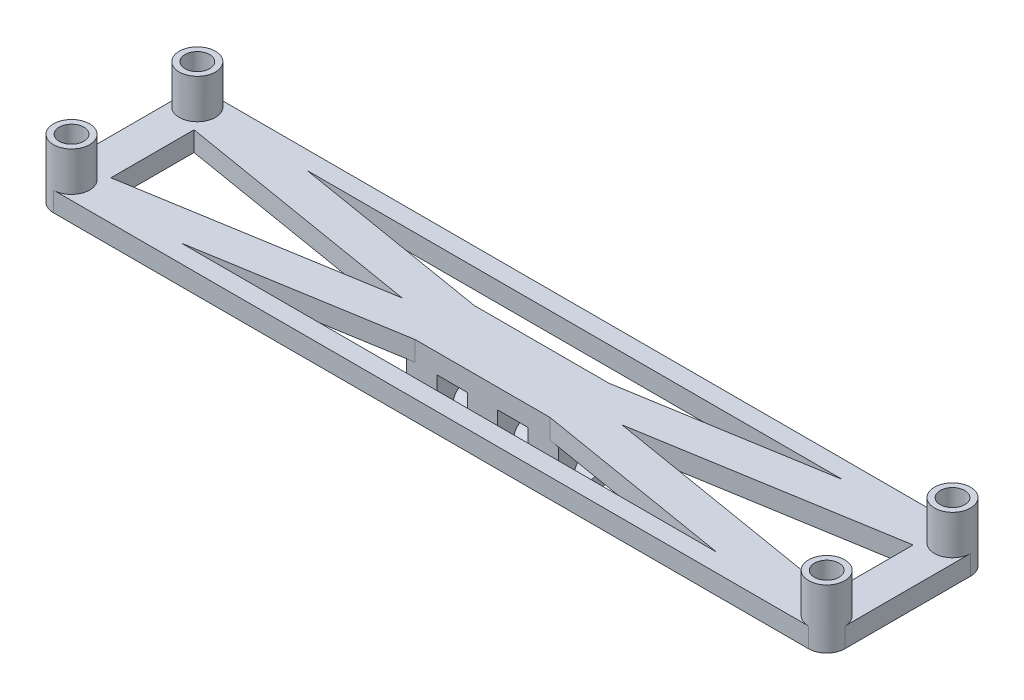
SolidWorks part; units mm, degrees
ref_plane "Front Plane" through (0, 0, 0) normal (0, 0, 1) x (1, 0, 0)
ref_plane "Top Plane" through (0, 0, 0) normal (0, 1, 0) x (1, 0, 0)
ref_plane "Right Plane" through (0, 0, 0) normal (1, 0, 0) x (0, 0, -1)
sketch "Sketch1" plane through (0, 0, 0) normal (0, 1, 0) x (1, 0, 0)
  line L1 (-38.36, 6.39) -> (-27.1925, 6.39) construction
  line L2 (-38.36, 6.39) -> (-38.36, -6.39) construction
  line L3 (-38.36, -6.39) -> (-36.525, -6.39) construction
  line L4 (38.36, 4.555) -> (38.36, 4.5297) construction
  line L7 (-38.0585, 8.2001) -> (-3.0899, 2.375) construction
  line L8 (-38.6615, 4.5799) -> (-11.1675, 0) construction
  line L10 (-38.6615, -4.5799) -> (-11.1675, 0) construction
  line L12 (11.1675, 0) -> (36.525, -4.224) construction
  line L13 (-3.0899, 2.375) -> (3.0899, 2.375) construction
  line L15 (-3.0899, -2.375) -> (3.0899, -2.375) construction
  line L17 (-38.36, 6.39) -> (-38.36, -6.39) construction
  line L18 (3.0899, 2.375) -> (16.1767, 4.555) construction
  line L19 (11.1675, 0) -> (36.525, 4.224) construction
  line L24 (3.0899, -2.375) -> (16.1767, -4.555) construction
  line L25 (-36.525, 6.39) -> (-36.525, -4.555) construction
  line L26 (-40.195, 6.39) -> (-40.195, -6.39) construction
  line L30 (-38.36, -6.39) -> (-36.525, -6.39) construction
  line L31 (-38.36, -4.555) -> (-36.525, -4.555) construction
  line L32 (-38.36, -8.225) -> (38.36, -8.225) construction
  line L33 (38.36, 4.555) -> (38.36, 4.5297) construction
  line L34 (40.195, 6.39) -> (40.195, -6.39) construction
  line L35 (36.525, 4.224) -> (36.525, -4.555) construction
  line L37 (16.1767, 4.555) -> (-38.36, 4.555) construction
  line L38 (38.36, 8.225) -> (-38.36, 8.225) construction
  line L39 (38.36, -4.5297) -> (38.6615, -4.5799) construction
  line L41 (-27.1925, 6.39) -> (-38.36, 6.39) construction
  line L42 (38.36, -4.5297) -> (38.36, -6.39) construction
  line L43 (38.36, -4.5297) -> (38.36, -6.39) construction
  line L44 (-16.1767, -4.555) -> (-3.0899, -2.375) construction
  line L45 (-16.1767, -4.555) -> (16.1767, -4.555) construction
  arc A0 (-38.0585, 8.2001) -> (-38.6615, 4.5799) centre (-38.36, 6.39) ccw construction
  arc A1 (38.0585, -8.2001) -> (38.6615, -4.5799) centre (38.36, -6.39) ccw construction
  arc A2 (-38.6615, -4.5799) -> (-38.0585, -8.2001) centre (-38.36, -6.39) ccw construction
  arc A3 (40.195, 6.39) -> (38.0585, 8.2001) centre (38.36, 6.39) ccw construction
  arc A4 (-36.525, 6.39) -> (-40.195, 6.39) centre (-38.36, 6.39) ccw construction
  arc A5 (-40.195, -6.39) -> (-36.525, -6.39) centre (-38.36, -6.39) ccw construction
  arc A8 (-38.36, -4.555) -> (-38.36, -8.225) centre (-38.36, -6.39) ccw construction
  arc A9 (38.36, -8.225) -> (38.36, -4.555) centre (38.36, -6.39) ccw construction
  arc A10 (40.195, 6.39) -> (38.0585, 8.2001) centre (38.36, 6.39) ccw construction
  arc A11 (38.0585, -8.2001) -> (40.195, -6.39) centre (38.36, -6.39) ccw construction
  arc A13 (-38.36, 8.225) -> (-38.36, 4.555) centre (-38.36, 6.39) ccw construction
  arc A14 (40.195, 6.39) -> (38.36, 8.225) centre (38.36, 6.39) ccw construction
  point P0 (0, 0)
  point P6 (0, 0)
  point P11 (0, 0)
  point P16 (0, 0)
  point P17 (-38.36, 0)
  point P26 (0, 6.39)
  point P35 (0, -6.39)
  point P43 (38.36, 0)
  dimension "D1" = 76.72
  dimension "D2" = 12.78
sketch "Sketch2" plane through (0, 0, 0) normal (0, 1, 0) x (1, 0, 0)
  line L0 (-38.36, 6.39) -> (38.36, -6.39) construction
  line L1 (38.36, -6.39) -> (-38.36, -6.39) construction
  line L2 (38.36, -6.39) -> (38.36, 6.39) construction
  line L3 (38.36, 6.39) -> (-38.36, 6.39) construction
  line L4 (-38.36, -6.39) -> (-38.36, 6.39) construction
  line L5 (38.36, -6.39) -> (-38.36, 6.39) construction
  line L6 (38.36, 6.39) -> (-38.36, -6.39) construction
  line L7 (-38.0585, 8.2001) -> (38.6615, -4.5799) construction
  line L8 (-38.6615, 4.5799) -> (38.0585, -8.2001) construction
  line L9 (-38.36, -6.39) -> (38.36, 6.39) construction
  line L10 (-38.6615, -4.5799) -> (38.0585, 8.2001) construction
  line L11 (-38.0585, -8.2001) -> (38.6615, 4.5799) construction
  line L12 (-38.36, 6.39) -> (-38.36, -6.39) construction
  line L19 (-36.525, 6.39) -> (-36.525, -6.39) construction
  line L20 (-40.195, 6.39) -> (-40.195, -6.39) construction
  line L21 (38.36, 6.39) -> (38.36, -6.39) construction
  line L22 (40.195, 6.39) -> (40.195, -6.39) construction
  line L23 (36.525, 6.39) -> (36.525, -6.39) construction
  line L24 (-38.36, 6.39) -> (38.36, 6.39) construction
  line L25 (-38.36, 8.225) -> (38.36, 8.225) construction
  line L26 (-38.36, 4.555) -> (38.36, 4.555) construction
  line L27 (-38.36, -6.39) -> (38.36, -6.39) construction
  line L28 (-38.36, -4.555) -> (38.36, -4.555) construction
  line L29 (-38.36, -8.225) -> (38.36, -8.225) construction
  line L31 (-7.715, 3) -> (7.715, 3)
  line L32 (-7.715, 3) -> (-7.715, -3)
  line L33 (-7.715, -3) -> (7.715, -3)
  line L34 (7.715, 3) -> (7.715, -3)
  line L35 (-7.715, 3) -> (7.715, -3) construction
  line L36 (-7.715, -3) -> (7.715, 3) construction
  arc A0 (-38.0585, 8.2001) -> (-38.6615, 4.5799) centre (-38.36, 6.39) ccw construction
  arc A1 (38.0585, -8.2001) -> (38.6615, -4.5799) centre (38.36, -6.39) ccw construction
  arc A2 (-38.6615, -4.5799) -> (-38.0585, -8.2001) centre (-38.36, -6.39) ccw construction
  arc A3 (38.6615, 4.5799) -> (38.0585, 8.2001) centre (38.36, 6.39) ccw construction
  arc A4 (-36.525, 6.39) -> (-40.195, 6.39) centre (-38.36, 6.39) ccw construction
  arc A5 (-40.195, -6.39) -> (-36.525, -6.39) centre (-38.36, -6.39) ccw construction
  arc A6 (40.195, 6.39) -> (36.525, 6.39) centre (38.36, 6.39) ccw construction
  arc A7 (36.525, -6.39) -> (40.195, -6.39) centre (38.36, -6.39) ccw construction
  arc A8 (-38.36, 8.225) -> (-38.36, 4.555) centre (-38.36, 6.39) ccw construction
  arc A9 (38.36, 4.555) -> (38.36, 8.225) centre (38.36, 6.39) ccw construction
  arc A10 (-38.36, -4.555) -> (-38.36, -8.225) centre (-38.36, -6.39) ccw construction
  arc A11 (38.36, -8.225) -> (38.36, -4.555) centre (38.36, -6.39) ccw construction
  point P0 (0, 0)
  point P7 (0, 0)
  point P12 (0, 0)
  point P17 (0, 0)
  point P18 (0, 0)
  point P25 (-38.36, 0)
  point P30 (38.36, 0)
  point P39 (0, 6.39)
  point P46 (0, -6.39)
  dimension "D1" = 15.43
  dimension "D2" = 6
sketch "Sketch3" plane through (0, 0, 0) normal (0, 1, 0) x (1, 0, 0)
  line L2 (6.8419, -3) -> (27.1925, -6.39)
  line L5 (-27.1925, 6.39) -> (-6.8419, 3)
  line L7 (-36.525, 4.224) -> (-36.525, -4.224)
  line L8 (-36.525, 6.39) -> (-36.525, -4.555) construction
  line L9 (-38.6615, 4.5799) -> (-11.1675, 0) construction
  line L10 (-38.6615, -4.5799) -> (-11.1675, 0) construction
  line L11 (-36.525, -4.224) -> (-11.1675, 0)
  line L12 (-11.1675, 0) -> (-36.525, 4.224)
  line L13 (6.8419, 3) -> (27.1925, 6.39)
  line L14 (38.36, 6.39) -> (-38.36, 6.39) construction
  line L15 (-38.6615, -4.5799) -> (38.0585, 8.2001) construction
  line L16 (27.1925, 6.39) -> (-27.1925, 6.39)
  line L17 (0, 0) -> (32.5589, 0) construction
  line L18 (-6.8419, -3) -> (6.8419, -3)
  line L19 (0, 0) -> (0, -14.525) construction
  line L20 (-27.1925, -6.39) -> (-6.8419, -3)
  line L21 (27.1925, -6.39) -> (-27.1925, -6.39)
  line L22 (36.525, -4.224) -> (11.1675, 0)
  line L23 (36.525, 4.224) -> (36.525, -4.224)
  line L24 (11.1675, 0) -> (36.525, 4.224)
  line L25 (-6.8419, 3) -> (6.8419, 3)
  line L26 (38.36, -8.225) -> (-38.36, -8.225)
  line L27 (40.195, -6.39) -> (40.195, 6.39)
  line L28 (38.36, 8.225) -> (-38.36, 8.225)
  line L29 (-40.195, -6.39) -> (-40.195, 6.39)
  line L30 (40.195, -8.225) -> (-40.195, 8.225) construction
  line L31 (40.195, 8.225) -> (-40.195, -8.225) construction
  arc A0 (-40.195, 6.39) -> (-38.36, 8.225) centre (-38.36, 6.39) cw
  arc A1 (38.36, -8.225) -> (40.195, -6.39) centre (38.36, -6.39) ccw
  arc A2 (40.195, 6.39) -> (38.36, 8.225) centre (38.36, 6.39) ccw
  arc A3 (-38.36, -8.225) -> (-40.195, -6.39) centre (-38.36, -6.39) cw
  dimension "D3" = 1.835
  dimension "D4" = 1.835
  dimension "D1" = 16.45
  dimension "D2" = 80.39
extrude "Boss-Extrude2" add sketch "Sketch3" along normal blind 2
sketch "Sketch4" plane through (0, 2, 0) normal (0, 1, 0) x (1, 0, 0)
  circle A0 centre (-38.36, 6.39) radius 1.835
  circle A1 centre (-38.36, -6.39) radius 1.835
  circle A2 centre (38.36, 6.39) radius 1.835
  circle A3 centre (38.36, -6.39) radius 1.835
extrude "Boss-Extrude3" add sketch "Sketch4" along normal blind 4
ref_plane "Plane1" through (0, 6, 0) normal (0, 1, 0) x (1, 0, 0)
sketch "Sketch6" plane through (0, 6, 0) normal (0, 1, 0) x (1, 0, 0)
  circle A0 centre (-38.36, 6.39) radius 1.25
  circle A1 centre (-38.36, -6.39) radius 1.25
  circle A2 centre (38.36, 6.39) radius 1.25
  circle A3 centre (38.36, -6.39) radius 1.25
  dimension "D1" = 2.5
extrude "Cut-Extrude1" cut sketch "Sketch6" against normal blind 4
ref_plane "Plane2" through (7.715, 0, 0) normal (-1, 0, 0) x (0, 0, 1)
sketch "Sketch7" plane through (7.715, 0, 0) normal (-1, 0, 0) x (0, 0, 1)
  line L0 (-3, 0) -> (3, 0) construction
  line L4 (-3, 0) -> (3, 0)
  line L5 (-3, -3.4) -> (-3, 0)
  line L6 (3, -3.4) -> (3, 0)
  circle A2 centre (0, -3.4) radius 1.375
  arc A3 (-3, -3.4) -> (3, -3.4) centre (0, -3.4) ccw
  dimension "D1" = 2.75
  dimension "D3" = 3.4
  dimension "D2" = 6
extrude "Boss-Extrude4" add sketch "Sketch7" along normal blind 3.086
pattern_linear "LPattern1" count 3 spacing 6.172 along (-1, 0, 0) of "Boss-Extrude4"
